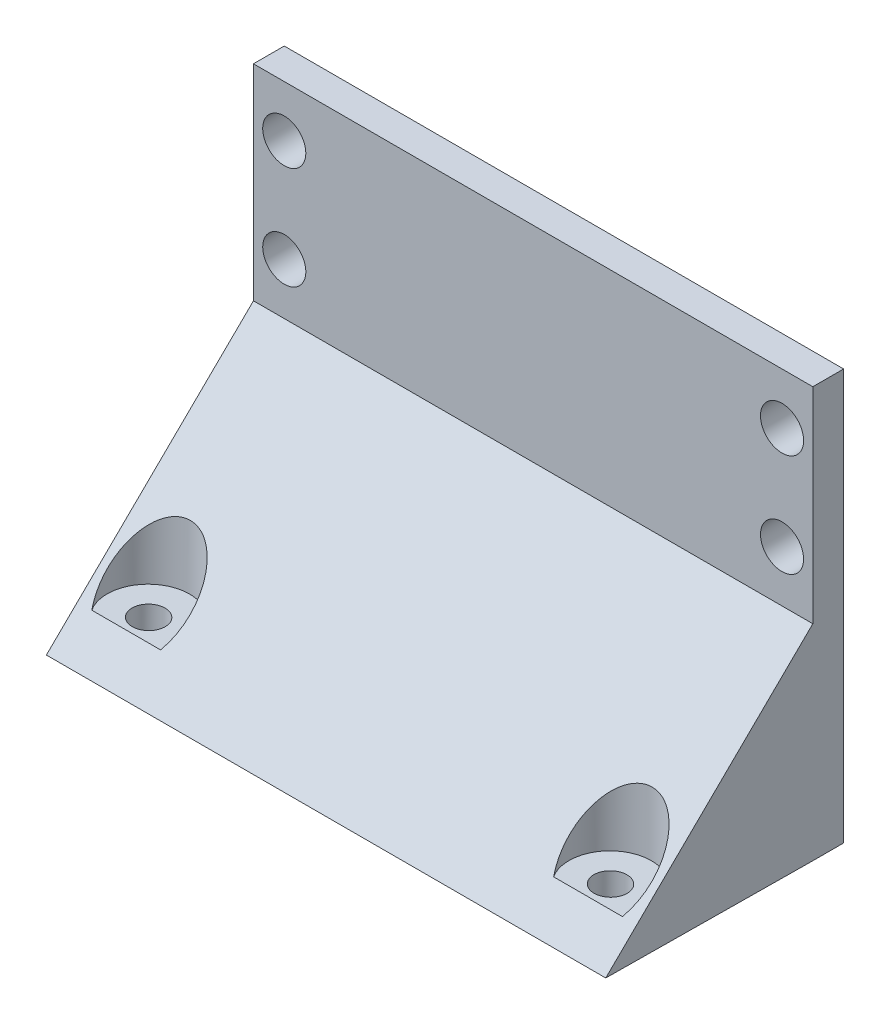
SolidWorks part; units mm, degrees
ref_plane "前视基准面" through (0, 0, 0) normal (0, 0, 1) x (1, 0, 0)
ref_plane "上视基准面" through (0, 0, 0) normal (0, 1, 0) x (1, 0, 0)
ref_plane "右视基准面" through (0, 0, 0) normal (1, 0, 0) x (0, 0, -1)
sketch "草图1" plane through (0, 0, 0) normal (0, 0, 1) x (1, 0, 0)
  line L0 (-24.25, 8.6666) -> (-24.25, -32.182) construction
  line L1 (-27.25, 0) -> (27.25, 0)
  line L2 (-27.25, 0) -> (-27.25, -40)
  line L3 (-27.25, -40) -> (27.25, -40)
  line L4 (27.25, 0) -> (27.25, -40)
  line L5 (-27.25, -20) -> (27.25, -20) construction
  line L6 (-33.3553, -10) -> (44.3008, -10) construction
  line L8 (0, 7.5998) -> (0, -20) construction
  circle A0 centre (-24.25, -5) radius 2.1
  circle A1 centre (24.25, -5) radius 2.1
  circle A2 centre (24.25, -15) radius 2.1
  circle A3 centre (-24.25, -15) radius 2.1
  point P0 (0, 0)
  point P9 (0, 0)
  dimension "D4" = 20
  dimension "D1" = 54.5
  dimension "D2" = 40
  dimension "D3" = 3
  dimension "D5" = 10
  dimension "D6" = 5
extrude "凸台-拉伸1" add sketch "草图1" along normal blind 3
sketch "草图2" plane through (-27.25, 0, 0) normal (-1, 0, 0) x (0, 0, 1)
  line L0 (3, -20) -> (23.1763, -39.8029)
  line L1 (3, 0) -> (3, -40) construction
  line L2 (3, -40) -> (23.1763, -39.8029)
  line L3 (3, -20) -> (3, -40)
extrude "凸台-拉伸2" add sketch "草图2" against normal up to surface (54.5 mm away) up to face at (27.25, -20, 1.5)
sketch "草图3" plane through (0, -40.0255, 0.3909) normal (0, -1, 0.0098) x (1, 0, 0)
  line L0 (0, -3.0489) -> (0, 13.8374) construction
  line L1 (-22.5, 17.6026) -> (22.5, 17.6026) construction
  line L2 (-22.5, 17.6026) -> (-22.5, 2.6026) construction
  line L3 (-22.5, 2.6026) -> (22.5, 2.6026) construction
  line L4 (22.5, 17.6026) -> (22.5, 2.6026) construction
  line L5 (-22.5, 17.6026) -> (22.5, 2.6026) construction
  line L6 (-22.5, 2.6026) -> (22.5, 17.6026) construction
  circle A0 centre (-22.5, 2.6026) radius 1.5
  circle A1 centre (-22.5, 17.6026) radius 1.6
  circle A2 centre (22.5, 17.6026) radius 1.6
  circle A3 centre (22.5, 2.6026) radius 1.5
  point P0 (0, 10.1026)
  point P12 (0, 0)
  dimension "D1" = 15
  dimension "D3" = 3
  dimension "D4" = 3
  dimension "D2" = 45
extrude "切除-拉伸1" cut sketch "草图3" against normal blind 8
sketch "草图4" plane through (0, -40.0255, 0.3909) normal (0, -1, 0.0098) x (1, 0, 0)
  circle A0 centre (-22.5, 17.6026) radius 4
  circle A1 centre (22.5, 17.6026) radius 4
  dimension "D1" = 8
  dimension "8" = 8
extrude "切除-拉伸2" cut sketch "草图4" along normal blind 7 from offset 10
